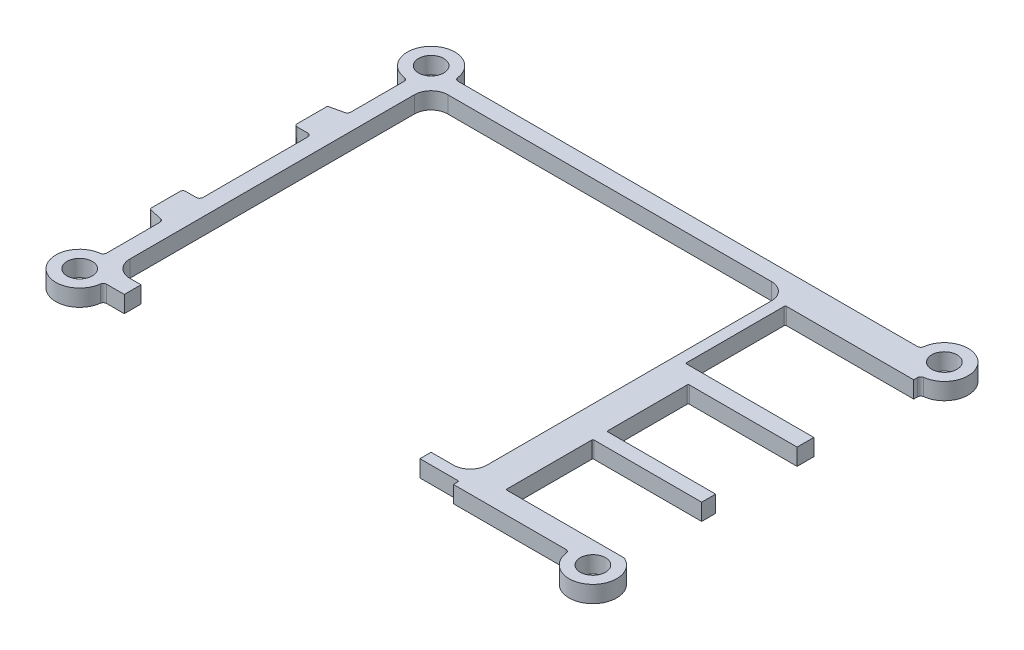
SolidWorks part; units mm, degrees
material "Balsa"
ref_plane "Front Plane" through (0, 0, 0) normal (0, 0, 1) x (1, 0, 0)
ref_plane "Top Plane" through (0, 0, 0) normal (0, 1, 0) x (1, 0, 0)
ref_plane "Right Plane" through (0, 0, 0) normal (1, 0, 0) x (0, 0, -1)
sketch "Sketch1" plane through (0, 0, 0) normal (0, 1, 0) x (1, 0, 0)
  line L0 (46, 0) -> (46, -63) construction
  line L5 (4.265, 0) -> (87.735, 0)
  line L6 (3.2, -3.25) -> (88.8, -3.25) construction
  line L7 (3.2, -3.25) -> (3.2, -59.75) construction
  line L8 (3.2, -59.75) -> (88.8, -59.75) construction
  line L9 (88.8, -3.25) -> (88.8, -59.75) construction
  line L10 (3.2, -3.25) -> (88.8, -59.75) construction
  line L11 (3.2, -59.75) -> (88.8, -3.25) construction
  line L12 (0, -4.265) -> (0, -58.735)
  line L14 (92, -4.265) -> (92, -58.735)
  line L15 (4.265, -63) -> (87.735, -63)
  circle A0 centre (0, 0) radius 2.265
  circle A1 centre (92, 0) radius 2.265
  circle A2 centre (92, -63) radius 2.265
  circle A3 centre (0, -63) radius 2.265
  arc A4 (4.265, 0) -> (0, -4.265) centre (0, 0) ccw
  arc A5 (92, -4.265) -> (87.735, 0) centre (92, 0) ccw
  arc A6 (87.735, -63) -> (92, -58.735) centre (92, -63) ccw
  arc A7 (0, -58.735) -> (4.265, -63) centre (0, -63) ccw
  point P7 (46, -31.5)
  dimension "D5" = 4.53
  dimension "D6" = 2
  dimension "D1" = 92
  dimension "D2" = 63
  dimension "D3" = 85.6
  dimension "D4" = 56.5
extrude "Boss-Extrude1" add sketch "Sketch1" along normal blind 3
sketch "Sketch2" plane through (0, 3, 0) normal (0, 1, 0) x (1, 0, 0)
  line L0 (0, -31.5) -> (92, -31.5) construction
  line L1 (0, -4.265) -> (0, -58.735) construction
  line L2 (92, -58.735) -> (92, -4.265) construction
  line L4 (0, -21.5) -> (6.5, -21.5)
  line L5 (0, -21.5) -> (0, -41.5)
  line L6 (0, -41.5) -> (6.5, -41.5)
  line L7 (6.5, -21.5) -> (6.5, -41.5)
  point P11 (0, -31.5)
  dimension "D1" = 20
  dimension "D2" = 6.5
extrude "Cut-Extrude1" cut sketch "Sketch2" against normal blind 3
sketch "Sketch3" plane through (0, 3, 0) normal (0, 1, 0) x (1, 0, 0)
  line L0 (-2.7, -15.5) -> (0, -14.9)
  line L1 (0, -21.5) -> (-2.5, -21.5)
  line L2 (0, -21.5) -> (0, -14.9)
  line L4 (-3, -21) -> (-3, -15.8)
  line L5 (6.5, -31.5) -> (-19.974, -31.5) construction
  line L6 (6.5, -41.5) -> (6.5, -21.5) construction
  line L7 (-3, -42) -> (-3, -47.2)
  line L8 (0, -41.5) -> (-2.5, -41.5)
  line L9 (0, -41.5) -> (0, -48.1)
  line L10 (-2.7, -47.5) -> (0, -48.1)
  arc A0 (-3, -21) -> (-2.5, -21.5) centre (-2.5, -21) ccw
  arc A1 (-3, -15.8) -> (-2.7, -15.5) centre (-2.7, -15.8) cw
  arc A2 (-3, -47.2) -> (-2.7, -47.5) centre (-2.7, -47.2) ccw
  arc A3 (-3, -42) -> (-2.5, -41.5) centre (-2.5, -42) cw
  point P7 (-3, -21.5)
  point P10 (-3, -15.5)
  dimension "D3" = 0.5
  dimension "D4" = 0.3
  dimension "D1" = 3
  dimension "D2" = 6
  dimension "D5" = 6.6
extrude "Boss-Extrude2" add sketch "Sketch3" against normal blind 3
sketch "Sketch4" plane through (0, 3, 0) normal (0, 1, 0) x (1, 0, 0)
  line L0 (0, -4.265) -> (0, -14.9) construction
  line L1 (6, -3) -> (64, -3)
  line L2 (3, -6) -> (3, -57)
  line L3 (6, -60) -> (64, -60)
  line L4 (67, -6) -> (67, -57)
  line L6 (4.265, -63) -> (87.735, -63) construction
  line L7 (87.735, 0) -> (4.265, 0) construction
  arc A0 (6, -60) -> (3, -57) centre (6, -57) cw
  arc A1 (67, -57) -> (64, -60) centre (64, -57) cw
  arc A2 (67, -6) -> (64, -3) centre (64, -6) ccw
  arc A3 (3, -6) -> (6, -3) centre (6, -6) cw
  dimension "D5" = 3
  dimension "D1" = 3
  dimension "D2" = 3
  dimension "D3" = 3
  dimension "D4" = 67
extrude "Cut-Extrude2" cut sketch "Sketch4" against normal blind 3
sketch "Sketch5" plane through (0, 3, 0) normal (0, 1, 0) x (1, 0, 0)
  line L0 (-2.5, -41.5) -> (3, -41.5) construction
  line L1 (3, -21.5) -> (0, -21.5)
  line L2 (3, -21.5) -> (3, -41.5)
  line L3 (3, -41.5) -> (0, -41.5)
  line L4 (0, -21.5) -> (0, -41.5)
extrude "Boss-Extrude3" add sketch "Sketch5" against normal blind 3
sketch "Sketch6" plane through (0, 3, 0) normal (0, 1, 0) x (1, 0, 0)
  line L0 (67, -57) -> (67, -6) construction
  line L1 (69, -5.5) -> (96.0101, -5.5)
  line L2 (69, -5.5) -> (69, -23.4)
  line L3 (69, -23.4) -> (96.0101, -23.4)
  line L4 (96.0101, -5.5) -> (96.0101, -23.4)
  line L5 (87.735, 0) -> (4.265, 0) construction
  dimension "D1" = 2
  dimension "D2" = 17.9
  dimension "D3" = 5.5
extrude "Cut-Extrude3" cut sketch "Sketch6" against normal blind 3
sketch "Sketch7" plane through (0, 3, 0) normal (0, 1, 0) x (1, 0, 0)
  line L0 (92, -58.735) -> (92, -23.4) construction
  line L1 (72.5, -26.4) -> (92, -26.4)
  line L2 (72.5, -26.4) -> (72.5, -41)
  line L3 (72.5, -41) -> (92, -41)
  line L4 (92, -26.4) -> (92, -41)
  line L5 (69, -23.4) -> (92, -23.4) construction
  line L6 (67, -57) -> (67, -6) construction
  line L7 (4.265, -63) -> (87.735, -63) construction
  dimension "D1" = 3
  dimension "D2" = 5.5
  dimension "D3" = 22
extrude "Cut-Extrude4" cut sketch "Sketch7" against normal blind 3
sketch "Sketch8" plane through (0, 3, 0) normal (0, 1, 0) x (1, 0, 0)
  line L0 (92, -58.735) -> (92, -41) construction
  line L1 (72.5, -43.5) -> (92, -43.5)
  line L2 (72.5, -43.5) -> (72.5, -59.1)
  line L3 (72.5, -59.1) -> (92, -59.1)
  line L4 (92, -43.5) -> (92, -59.1)
  line L5 (72.5, -41) -> (92, -41) construction
  line L6 (67, -57) -> (67, -6) construction
  line L7 (4.265, -63) -> (87.735, -63) construction
  dimension "D1" = 2.5
  dimension "D2" = 5.5
  dimension "D3" = 3.9
extrude "Cut-Extrude5" cut sketch "Sketch8" against normal blind 3
sketch "Sketch9" plane through (0, 3, 0) normal (0, 1, 0) x (1, 0, 0)
  line L1 (92, -59.1) -> (94.0196, -59.1)
  line L2 (92, -59.1) -> (92, -58.5257)
  line L3 (92, -58.5257) -> (94.0196, -58.5257)
  line L4 (94.0196, -59.1) -> (94.0196, -58.5257)
extrude "Cut-Extrude6" cut sketch "Sketch9" against normal blind 3
sketch "Sketch10" plane through (0, 3, 0) normal (0, 1, 0) x (1, 0, 0)
  line L0 (6, -60) -> (64, -60) construction
  line L1 (8, -60) -> (60, -60)
  line L2 (8, -60) -> (8, -63)
  line L3 (8, -63) -> (60, -63)
  line L4 (60, -60) -> (60, -63)
  line L5 (4.265, -63) -> (87.735, -63) construction
  line L6 (3, -6) -> (3, -57) construction
  dimension "D1" = 5
  dimension "D2" = 52
extrude "Cut-Extrude7" cut sketch "Sketch10" against normal blind 3
sketch "Sketch11" plane through (0, 3, 0) normal (0, 1, 0) x (1, 0, 0)
  line L1 (60, -63) -> (67, -63)
  line L2 (60, -63) -> (60, -62)
  line L3 (60, -62) -> (67, -62)
  line L4 (67, -63) -> (67, -62)
  dimension "D1" = 7
  dimension "D2" = 1
extrude "Cut-Extrude8" cut sketch "Sketch11" against normal blind 3
fillet "Fillet1" radius 0.6 12 edges at (87.735, 1.5, 0) (92, 1.5, 4.265) (93.7263, 1.5, 59.1) (87.735, 1.5, 63) (4.265, 1.5, 63) (0, 1.5, 58.735) (0, 1.5, 48.1) (0, 1.5, 41.5) (4.265, 1.5, 0) (0, 1.5, 14.9) (0, 1.5, 4.265) (0, 1.5, 21.5)
fillet "Fillet2" radius 0.2 7 edges at (67, 1.5, 62) (69, 1.5, 5.5) (69, 1.5, 23.4) (72.5, 1.5, 26.4) (72.5, 1.5, 41) (72.5, 1.5, 43.5) (72.5, 1.5, 59.1)
